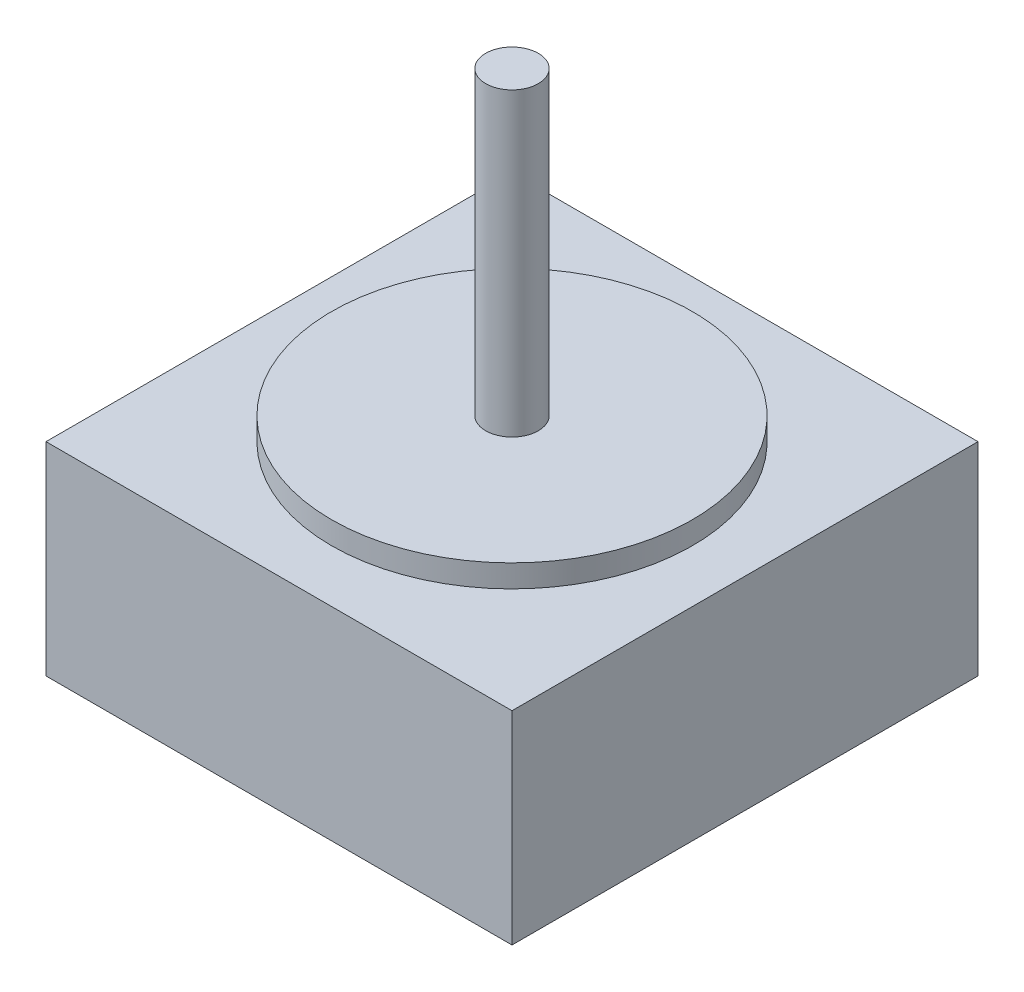
SolidWorks part; units mm, degrees
ref_plane "Plan de face" through (0, 0, 0) normal (0, 0, 1) x (1, 0, 0)
ref_plane "Plan de dessus" through (0, 0, 0) normal (0, 1, 0) x (1, 0, 0)
ref_plane "Plan de droite" through (0, 0, 0) normal (1, 0, 0) x (0, 0, -1)
sketch "Esquisse2" plane through (0, 0, 0) normal (0, 1, 0) x (1, 0, 0)
  line L1 (-31, -31) -> (31, -31)
  line L2 (-31, -31) -> (-31, 31)
  line L3 (-31, 31) -> (31, 31)
  line L4 (31, -31) -> (31, 31)
  line L5 (-31, -31) -> (31, 31) construction
  line L6 (-31, 31) -> (31, -31) construction
  point P0 (0, 0)
  dimension "D1" = 62
  dimension "D2" = 62
extrude "Boss.-Extru.1" add sketch "Esquisse2" along normal blind 27
sketch "Esquisse3" plane through (0, 27, 0) normal (0, 1, 0) x (1, 0, 0)
  circle A0 centre (0, 0) radius 24
  dimension "D1" = 48
extrude "Boss.-Extru.2" add sketch "Esquisse3" along normal blind 3
sketch "Esquisse4" plane through (0, 30, 0) normal (0, 1, 0) x (1, 0, 0)
  circle A0 centre (0, 0) radius 3.5
  dimension "D1" = 7
extrude "Boss.-Extru.3" add sketch "Esquisse4" along normal blind 40
